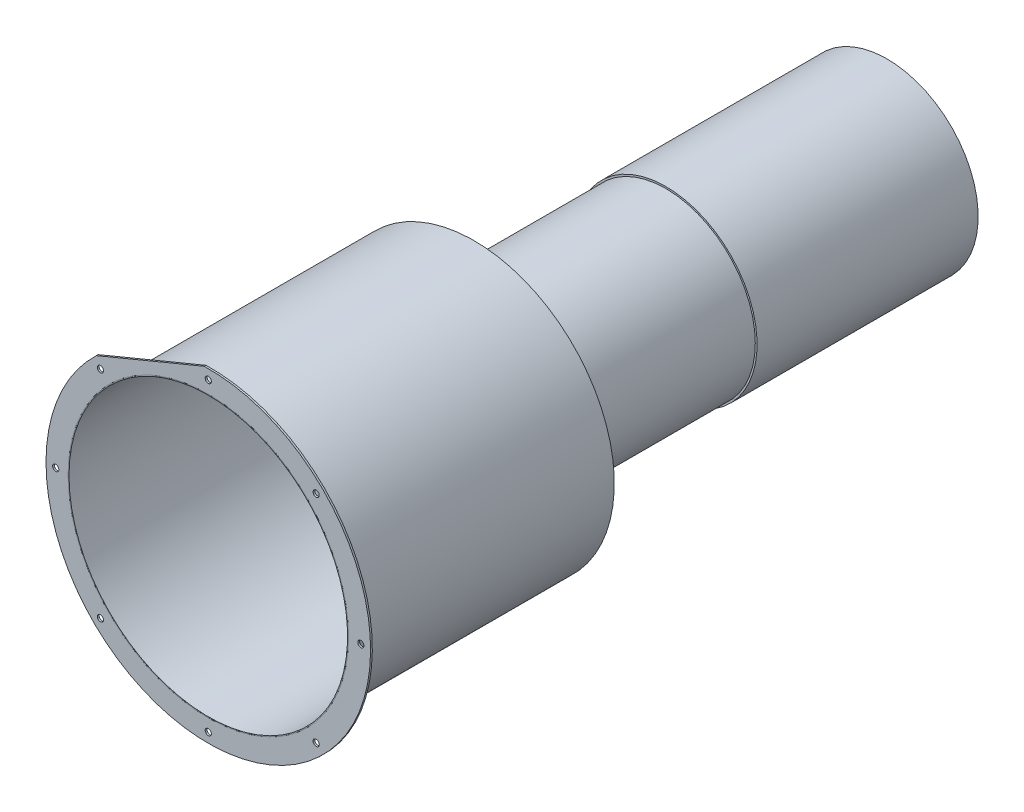
SolidWorks part; units mm, degrees
material "Galvanized Steel"
ref_plane "Front Plane" through (0, 0, 0) normal (0, 0, 1) x (1, 0, 0)
ref_plane "Top Plane" through (0, 0, 0) normal (0, 1, 0) x (1, 0, 0)
ref_plane "Right Plane" through (0, 0, 0) normal (1, 0, 0) x (0, 0, -1)
sketch "Sketch1" plane through (0, 0, 0) normal (1, 0, 0) x (0, 0, -1)
  line L0 (-767.5, 157.5) -> (-467.5, 157.5)
  line L1 (-467.5, 157.5) -> (-434.3024, 100)
  line L2 (-434.3024, 100) -> (0, 100)
  line L3 (0, 0) -> (-943.6148, 0) construction
  dimension "D1" = 300
  dimension "D2" = 767.5
  dimension "D3" = 120
  dimension "D4" = 315
  dimension "D5" = 200
revolve "Revolve-Thin1" add sketch "Sketch1" angle 360 about L3 wall 1
sketch "Sketch2" plane through (0, 0, 0) normal (0, 0, -1) x (-1, 0, 0)
  circle A0 centre (0, 0) radius 101 construction
  circle A1 centre (0, 0) radius 101
extrude "Extrude-Thin1" add sketch "Sketch2" against normal blind 250 thin
sketch "Sketch3" plane through (0, 0, 767.5) normal (0, 0, 1) x (1, 0, 0)
  circle A0 centre (0, 0) radius 158.5 construction
  circle A1 centre (0, 0) radius 158.5
  circle A2 centre (0, 0) radius 183.5
  dimension "D1" = 25
extrude "Extrude1" add sketch "Sketch3" against normal blind 2 separate body
sketch "Sketch4" plane through (0, 0, 767.5) normal (0, 0, 1) x (1, 0, 0)
  line L0 (0, 0) -> (210.9186, 0) construction
  circle A0 centre (172.5, 0) radius 3.5
  circle A1 centre (0, 0) radius 172.5 construction
  dimension "D1" = 7
  dimension "D2" = 345
extrude "Extrude2" cut sketch "Sketch4" against normal blind 2
pattern_circular "CirPattern1" count 8 over 360 about axis through (0, 0, 0) along (0, 0, 1) of "Extrude2"
sketch "Sketch5" plane through (0, 0, 765.5) normal (0, 0, -1) x (-1, 0, 0)
  line L1 (0, 172.5) -> (121.9759, 121.9759) construction
  line L2 (121.9759, 121.9759) -> (131.9695, 146.1026) construction
  line L3 (0, 172.5) -> (11.3898, 199.9974) construction
  line L4 (4.5332, 183.444) -> (126.5091, 132.9199)
  circle A0 centre (0, 0) radius 183.5 construction
  arc A1 (126.5091, 132.9199) -> (4.5332, 183.444) centre (0, 0) ccw
extrude "Extrude3" cut sketch "Sketch5" against normal blind 10
